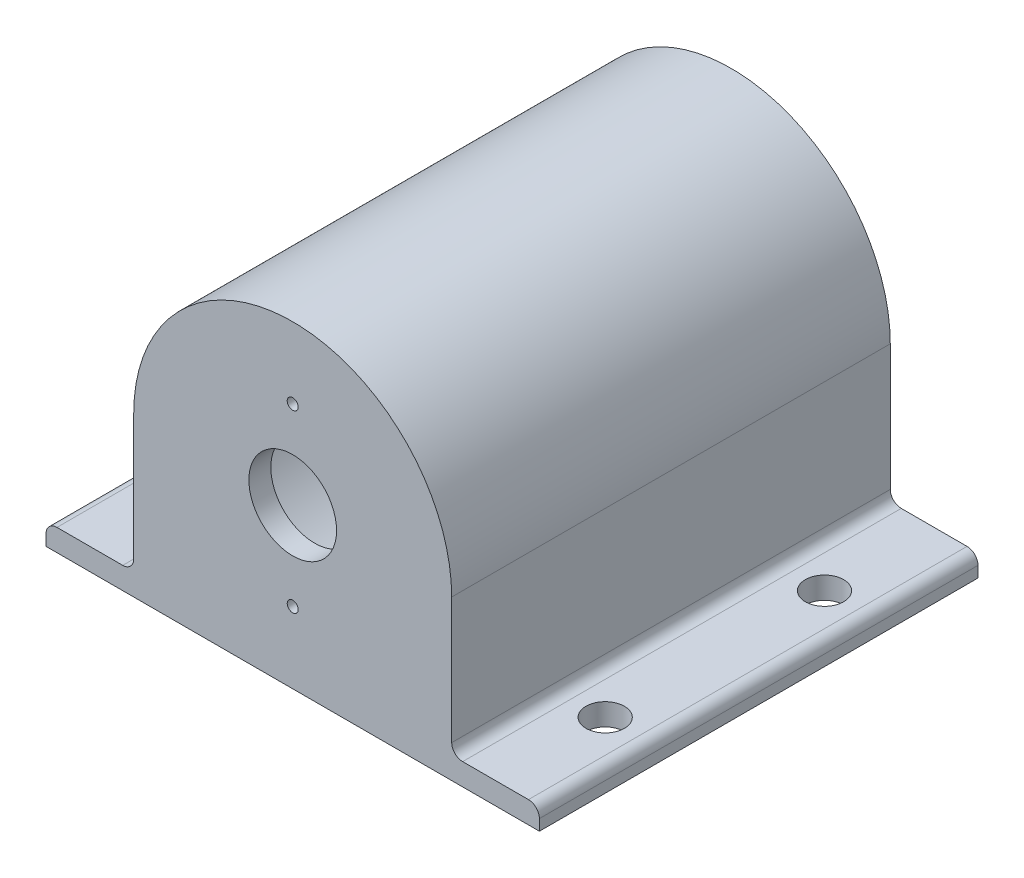
SolidWorks part; units mm, degrees
ref_plane "Plan de face" through (0, 0, 0) normal (0, 0, 1) x (1, 0, 0)
ref_plane "Plan de dessus" through (0, 0, 0) normal (0, 1, 0) x (1, 0, 0)
ref_plane "Plan de droite" through (0, 0, 0) normal (1, 0, 0) x (0, 0, -1)
sketch "Esquisse1" plane through (0, 0, 0) normal (0, 0, 1) x (1, 0, 0)
  line L0 (-14.5, 0) -> (14.5, 0)
  circle A0 centre (0, 0) radius 12.5
  circle A1 centre (0, 0) radius 14.5
  dimension "D1" = 25
  dimension "D2" = 29
extrude "Boss.-Extru.1" add sketch "Esquisse1" along normal blind 40 contours L0 A1 A0
sketch "Esquisse2" plane through (0, 0, 0) normal (0, -1, 0) x (1, 0, 0)
  line L1 (-14.5, 40) -> (-12.5, 40)
  line L2 (-14.5, 40) -> (-14.5, 0)
  line L3 (-14.5, 0) -> (-12.5, 0)
  line L4 (-12.5, 40) -> (-12.5, 0)
  line L5 (14.5, 0) -> (12.5, 0)
  line L6 (14.5, 0) -> (14.5, 40)
  line L7 (14.5, 40) -> (12.5, 40)
  line L8 (12.5, 0) -> (12.5, 40)
extrude "Boss.-Extru.2" add sketch "Esquisse2" along normal blind 12.5
sketch "Esquisse4" plane through (0, 0, 40) normal (0, 0, 1) x (1, 0, 0)
  line L1 (-12.5, -12.5) -> (12.5, -12.5)
  line L2 (-12.5, -12.5) -> (-12.5, 0)
  line L3 (-12.5, 0) -> (12.5, 0)
  line L4 (12.5, -12.5) -> (12.5, 0)
  circle A0 centre (0, 0) radius 12.5
  circle A1 centre (0, 0) radius 4
  line M8 (-12.5, -12.5) -> (-12.5, 0)
  arc M9 (-12.5, 0) -> (12.5, 0) centre (0, 0) cw
  line M10 (12.5, 0) -> (12.5, -12.5)
  dimension "D1" = 8
  dimension "D2" = 25
extrude "Boss.-Extru.4" add sketch "Esquisse4" against normal blind 2 contours A1 L3 M9 | A1 L3 A0 | A0 L1 M8 | A0 L1 M10
sketch "Esquisse5" plane through (0, 0, 40) normal (0, 0, 1) x (1, 0, 0)
  line L0 (0, -8) -> (0, 8)
  circle A0 centre (0, 0) radius 8
  circle A1 centre (0, -8) radius 0.5
  circle A2 centre (0, 8) radius 0.5
  dimension "D1" = 16
  dimension "D2" = 1
  dimension "D3" = 1
extrude "Enlèv. mat.-Extru.1" cut sketch "Esquisse5" against normal through all contours A2 | A1
sketch "Esquisse8" plane through (0, 0, 40) normal (0, 0, 1) x (1, 0, 0)
  line L0 (-14.5, -12.5) -> (-22.5, -12.5)
  line L1 (-22.5, -12.5) -> (-22.5, -14.5)
  line L2 (-22.5, -14.5) -> (22.5, -14.5)
  line L3 (22.5, -14.5) -> (22.5, -12.5)
  line L4 (22.5, -12.5) -> (14.5, -12.5)
  line L5 (14.5, -12.5) -> (-14.5, -12.5)
  line L6 (12.5, -12.5) -> (12.5, 0) construction
  line L7 (-12.5, -12.5) -> (-12.5, 0) construction
  dimension "D1" = 10
  dimension "D2" = 10
  dimension "D3" = 2
extrude "Boss.-Extru.13" add sketch "Esquisse8" against normal blind 40
sketch "Esquisse9" plane through (0, 0, 38) normal (0, 0, -1) x (-1, 0, 0)
  line L1 (-12.5, -12.5) -> (12.5, -12.5)
  line L2 (-12.5, -12.5) -> (-12.5, 0)
  line L3 (-12.5, 0) -> (12.5, 0)
  line L4 (12.5, -12.5) -> (12.5, 0)
  circle A0 centre (0, 0) radius 12.5
  line M4 (-12.5, 0) -> (-12.5, -12.5)
  line M5 (-12.5, -12.5) -> (12.5, -12.5)
  line M6 (12.5, -12.5) -> (12.5, 0)
extrude "Boss.-Extru.14" add sketch "Esquisse9" along normal blind 38 contours A0 M4 M5 | A0 L1 M6
fillet "Congé1" radius 1 4 edges at (-14.5, -12.5, 20) (14.5, -12.5, 20) (-22.5, -12.5, 20) (22.5, -12.5, 20)
sketch "Esquisse10" plane through (0, -12.5, 0) normal (0, 1, 0) x (1, 0, 0)
  line L1 (0, 0) -> (0, 4.2816)
  line L2 (-15.5, 0) -> (-21.5, 0) construction
  line L3 (-15.5, -40) -> (-21.5, -40) construction
  line L4 (-21.5, 0) -> (-21.5, -40) construction
  circle A0 centre (-18.5, -10) radius 1.75
  circle A1 centre (-18.5, -30) radius 1.75
  circle A2 centre (18.5, -30) radius 1.75
  circle A3 centre (18.5, -10) radius 1.75
  dimension "D1" = 3.5
  dimension "D2" = 3.5
  dimension "D3" = 10
  dimension "D4" = 10
  dimension "D5" = 3
  dimension "D6" = 3
extrude "Enlèv. mat.-Extru.2" cut sketch "Esquisse10" against normal through all contours A0 | A1 | A2 | A3
sketch "Esquisse11" plane through (0, -14.5, 0) normal (0, -1, 0) x (1, 0, 0)
  line L0 (0, 0) -> (0, 3.2685)
  circle A0 centre (-18.5, 30) radius 1.75
  circle A1 centre (-18.5, 10) radius 1.75
  circle A2 centre (18.5, 10) radius 1.75
  circle A3 centre (18.5, 30) radius 1.75
  dimension "D1" = 3.5
  dimension "D2" = 3.5
